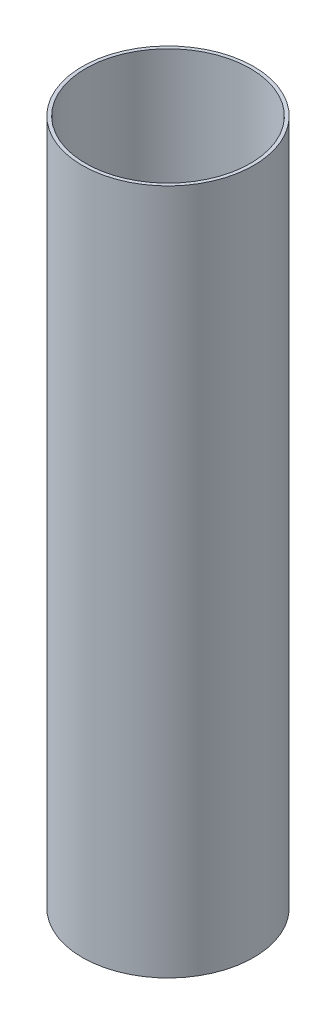
SolidWorks part; units mm, degrees
ref_plane "Front Plane" through (0, 0, 0) normal (0, 0, 1) x (1, 0, 0)
ref_plane "Top Plane" through (0, 0, 0) normal (0, 1, 0) x (1, 0, 0)
ref_plane "Right Plane" through (0, 0, 0) normal (1, 0, 0) x (0, 0, -1)
sketch "Sketch1" plane through (0, 0, 0) normal (0, 1, 0) x (1, 0, 0)
  circle A0 centre (0, 0) radius 38.1
  circle A1 centre (0, 0) radius 39.6748
  dimension "D1" = 76.2
  dimension "D2" = 79.3496
extrude "Boss-Extrude1" add sketch "Sketch1" along normal mid plane 317.5
equation "\"airframeInnerDiameter\"=3"
equation "\"outerDiameter\"=3.124"
equation "\"upperAirframeLength\"=12.5"
equation "\"D1@Sketch1\"=\"airframeInnerDiameter\""
equation "\"D2@Sketch1\"=\"outerDiameter\""
equation "\"D1@Boss-Extrude1\"=\"upperAirframeLength\""
